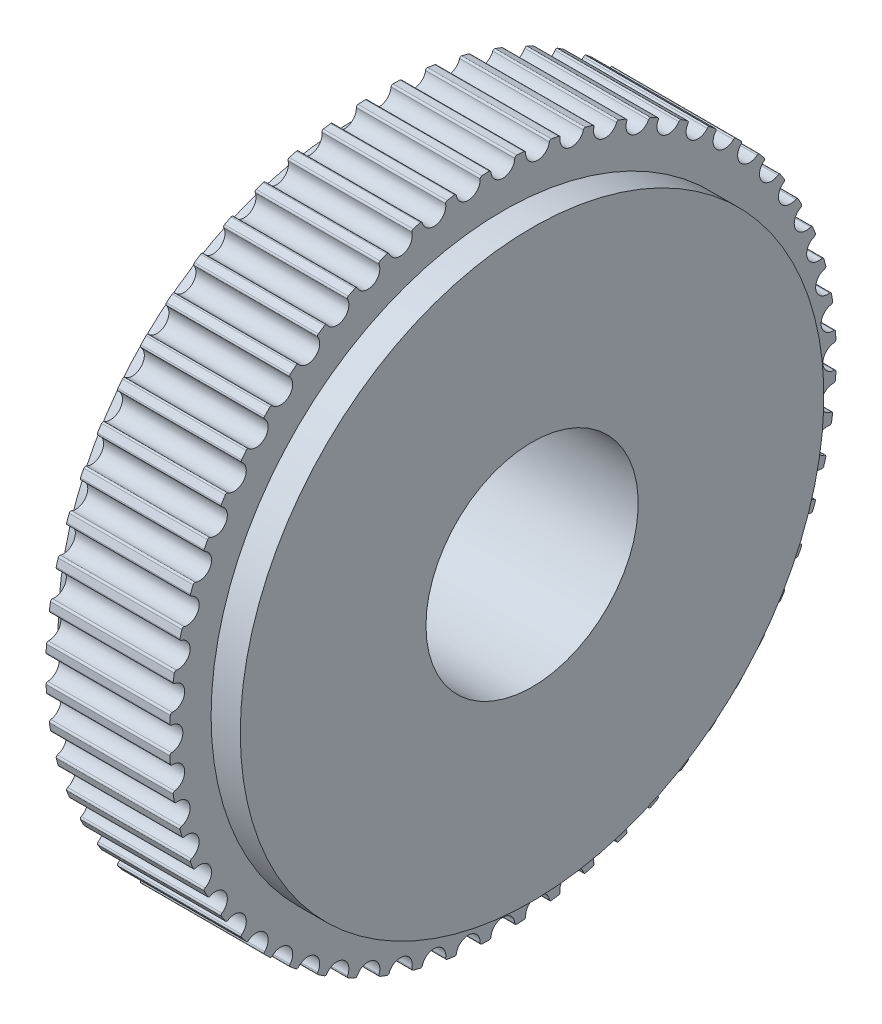
SolidWorks part; units mm, degrees
ref_plane "Front Plane" through (0, 0, 0) normal (0, 0, 1) x (1, 0, 0)
ref_plane "Top Plane" through (0, 0, 0) normal (0, 1, 0) x (1, 0, 0)
ref_plane "Right Plane" through (0, 0, 0) normal (1, 0, 0) x (0, 0, -1)
sketch "Sketch1" plane through (0, 0, 0) normal (0, 0, 1) x (1, 0, 0)
  line L0 (1.65, 19.1) -> (8.65, 19.1) construction
  line L1 (1.65, 18.845) -> (8.65, 18.845)
  line L2 (0, 16.5) -> (0, 6)
  line L4 (10.3, 16.5) -> (10.3, 6)
  line L5 (0, 6) -> (10.3, 6)
  line L6 (0, 0) -> (10.3, 0) construction
  line L8 (1.65, 16.5) -> (0, 16.5)
  line L9 (8.65, 16.5) -> (8.65, 18.845)
  line L10 (10.3, 16.5) -> (8.65, 16.5)
  line L13 (1.65, 16.5) -> (1.65, 18.845)
  dimension "W" = 10.3
  dimension "A" = 7
  dimension "E" = 33
  dimension "P.D." = 38.2
  dimension "H" = 12
revolve "Revolve1" add sketch "Sketch1" angle 360 about L6
sketch "Sketch2" plane through (1.65, 0, 0) normal (1, 0, 0) x (0, 0, -1)
  line L0 (0, 0) -> (0, 18.845) construction
  circle A0 centre (0, 0) radius 18.845 construction
  circle A1 centre (0, 0) radius 18.845 construction
  arc A2 (0.6721, 18.833) -> (-0.6721, 18.833) centre (0, 0) ccw
  arc A3 (-0.6721, 18.833) -> (0.6721, 18.833) centre (0, 18.77) ccw
  circle A6 centre (0, 0) radius 18.095 construction
  circle A7 centre (0, 0) radius 19.099 construction
  dimension "MSM_3" = 0.675
  dimension "MSM_2" = 0.254
  dimension "MSM_1" = 0.75
extrude "Cut-Extrude1" cut sketch "Sketch2" along normal through all
fillet "Fillet1" radius 0.1 2 edges at (5.15, 18.833, -0.6721) (5.15, 18.833, 0.6721)
pattern_circular "CirPattern1" count 60 over 360 about axis through (0, 0, 0) along (1, 0, 0) of "Cut-Extrude1", "Fillet1"
hole_wizard "Tapped Hole2" [suppressed] positions "Sketch9" profile "Sketch8" tap size "M3x0.5" standard "JIS"
sketch "Sketch9" [suppressed] plane through (10.3, 8.8848, 0.534) normal (1, 0, 0) x (0, 0, -1)
  line L2 (0.534, -8.8848) -> (0.534, -16.8848) construction
  line L3 (0.534, -8.8848) -> (-6.3942, -4.8848) construction
  circle A0 centre (0.534, -8.8848) radius 8 construction
  point P0 (0.534, -16.8848)
  point P23 (-6.3942, -4.8848)
  point P24 (7.4622, -4.8848)
  dimension "QTC" = 16
  dimension "Angle_2" = 120
  dimension "Number" = 3
sketch "Sketch8" [suppressed] plane through (10.3, -8, 0) normal (0, 1, 0) x (0, 0, -1)
  line L0 (0, 0) -> (0, 9.2511)
  line L1 (0, 9.2511) -> (1.25, 8.5)
  line L2 (1.25, 8.5) -> (1.25, 0)
  line L5 (1.25, 0) -> (0, 0)
  line L10 (0, 9.2511) -> (-1.25, 8.5) construction
  line L11 (0, 0) -> (0, 9.2511) construction
  dimension "Tap Drill Dia." = 2.5
  dimension "Tap Drill Depth" = 8.5
  dimension "Drill Angle" = 118
cosmetic thread "Hole Thread2" [suppressed] parameters "Mx2"=6, "M"=3
cosmetic thread "Hole Thread3" [suppressed] parameters "Mx2"=6, "M"=3
cosmetic thread "Hole Thread4" [suppressed] parameters "Mx2"=6, "M"=3
hole_wizard "Tapped Hole3" [suppressed] positions "Sketch11" profile "Sketch10" tap size "M3x0.5" standard "JIS"
sketch "Sketch11" [suppressed] plane through (10.3, 6.1168, -5.003) normal (1, 0, 0) x (0, 0, -1)
  line L3 (-5.003, -6.1168) -> (-10.6598, -11.7737) construction
  line L4 (-5.003, -6.1168) -> (-10.6598, -0.46) construction
  line L5 (-5.003, 1.8832) -> (-5.003, -14.1168) construction
  circle A0 centre (-5.003, -6.1168) radius 8 construction
  point P22 (-10.6598, -11.7737)
  point P23 (6.0104, 6.0104)
  point P27 (-10.6598, -0.46)
  point P28 (0.6539, -0.46)
  point P29 (0.6539, -11.7737)
  dimension "QFC" = 16
  dimension "Angle_2" = 90
  dimension "Angle_1" = 45
  dimension "Number" = 4
sketch "Sketch10" [suppressed] plane through (10.3, -5.6569, 5.6569) normal (0, 1, 0) x (0, 0, -1)
  line L0 (0, 0) -> (0, 9.2511)
  line L1 (0, 9.2511) -> (1.25, 8.5)
  line L2 (1.25, 8.5) -> (1.25, 0)
  line L5 (1.25, 0) -> (0, 0)
  line L10 (0, 9.2511) -> (-1.25, 8.5) construction
  line L11 (0, 0) -> (0, 9.2511) construction
  dimension "Tap Drill Dia." = 2.5
  dimension "Tap Drill Depth" = 8.5
  dimension "Drill Angle" = 118
cosmetic thread "Hole Thread5" [suppressed] parameters "Mx2"=6, "M"=3
cosmetic thread "Hole Thread6" [suppressed] parameters "Mx2"=6, "M"=3
cosmetic thread "Hole Thread7" [suppressed] parameters "Mx2"=6, "M"=3
cosmetic thread "Hole Thread8" [suppressed] parameters "Mx2"=6, "M"=3
hole_wizard "Tapped Hole4" [suppressed] positions "Sketch13" profile "Sketch12" tap size "M3x0.5" standard "JIS"
sketch "Sketch13" [suppressed] plane through (10.3, 0, 0) normal (1, 0, 0) x (0, 0, -1)
  line L0 (0, 0) -> (0, 8) construction
  line L2 (0, 0) -> (-3.3809, 7.2505) construction
  line L4 (0, 0) -> (4.5886, 6.5532) construction
  circle A0 centre (0, 0) radius 8 construction
  point P0 (-3.3809, 7.2505)
  point P33 (4.5886, 6.5532)
  point P34 (7.9696, -0.6972)
  point P35 (3.3809, -7.2505)
  point P36 (-4.5886, -6.5532)
  point P37 (-7.9696, 0.6972)
  point P38 (0, 0)
  dimension "QSC" = 16
  dimension "Angle_1" = 35
  dimension "Angle_2" = 60
  dimension "Number" = 6
sketch "Sketch12" [suppressed] plane through (10.3, 7.2505, 3.3809) normal (0, 1, 0) x (0, 0, -1)
  line L0 (0, 0) -> (0, 9.2511)
  line L1 (0, 9.2511) -> (1.25, 8.5)
  line L2 (1.25, 8.5) -> (1.25, 0)
  line L5 (1.25, 0) -> (0, 0)
  line L10 (0, 9.2511) -> (-1.25, 8.5) construction
  line L11 (0, 0) -> (0, 9.2511) construction
  dimension "Tap Drill Dia." = 2.5
  dimension "Tap Drill Depth" = 8.5
  dimension "Drill Angle" = 118
cosmetic thread "Hole Thread9" [suppressed] parameters "Mx2"=6, "M"=3
cosmetic thread "Hole Thread10" [suppressed] parameters "Mx2"=6, "M"=3
cosmetic thread "Hole Thread11" [suppressed] parameters "Mx2"=6, "M"=3
cosmetic thread "Hole Thread12" [suppressed] parameters "Mx2"=6, "M"=3
cosmetic thread "Hole Thread13" [suppressed] parameters "Mx2"=6, "M"=3
cosmetic thread "Hole Thread14" [suppressed] parameters "Mx2"=6, "M"=3
hole_wizard "Diameter Hole1" [suppressed] positions "Sketch15" profile "Sketch14" hole size "Ø4.0" standard "JIS"
sketch "Sketch15" [suppressed] plane through (0, 0, 0) normal (1, 0, 0) x (0, 0, -1)
  line L11 (0, 0) -> (0, -8) construction
  line L12 (0, 0) -> (-6.9282, 4) construction
  circle A2 centre (0, 0) radius 8 construction
  point P16 (0, -8)
  point P80 (-6.9282, 4)
  point P81 (6.9282, 4)
  dimension "D1" = 120
  dimension "KTC" = 16
  dimension "D2" = 3
sketch "Sketch14" [suppressed] plane through (0, -8, 0) normal (0, 1, 0) x (0, 0, 1)
  line L0 (0, 0) -> (0, 10.3)
  line L1 (0, 10.3) -> (2, 10.3)
  line L2 (2, 10.3) -> (2, 0)
  line L5 (2, 0) -> (0, 0)
  line L11 (0, 0) -> (0, 10.3) construction
  dimension "K" = 4
  dimension "Thru Hole Depth" = 10.3
hole_wizard "Diameter Hole2" [suppressed] positions "Sketch17" profile "Sketch16" hole size "Ø4.0" standard "JIS"
sketch "Sketch17" [suppressed] plane through (0, 0, 0) normal (1, 0, 0) x (0, 0, -1)
  line L18 (0, 0) -> (-5.6569, -5.6569) construction
  line L19 (0, 0) -> (-5.6569, 5.6569) construction
  line L20 (0, 8) -> (0, -8) construction
  circle A2 centre (0, 0) radius 8 construction
  point P104 (-5.6569, -5.6569)
  point P120 (-6.364, 6.364)
  point P146 (-5.6569, 5.6569)
  point P147 (5.6569, 5.6569)
  point P148 (5.6569, -5.6569)
  dimension "D1" = 90
  dimension "KFC" = 16
  dimension "D2" = 45
  dimension "D3" = 4
sketch "Sketch16" [suppressed] plane through (0, -5.6569, 5.6569) normal (0, 1, 0) x (0, 0, 1)
  line L0 (0, 0) -> (0, 10.3)
  line L1 (0, 10.3) -> (2, 10.3)
  line L2 (2, 10.3) -> (2, 0)
  line L5 (2, 0) -> (0, 0)
  line L11 (0, 0) -> (0, 10.3) construction
  dimension "K" = 4
  dimension "Thru Hole Depth" = 10.3
hole_wizard "Diameter Hole3" [suppressed] positions "Sketch19" profile "Sketch18" hole size "Ø4.0" standard "JIS"
sketch "Sketch19" [suppressed] plane through (0, 0, 0) normal (-1, 0, 0) x (0, 0, 1)
  line L0 (0, 8) -> (0, 0) construction
  line L1 (0, 0) -> (3.3809, 7.2505) construction
  line L3 (0, 0) -> (-4.5886, 6.5532) construction
  circle A0 centre (0, 0) radius 8 construction
  point P0 (-4.5886, 6.5532)
  point P23 (3.3809, 7.2505)
  point P24 (7.9696, 0.6972)
  point P25 (4.5886, -6.5532)
  point P26 (-3.3809, -7.2505)
  point P27 (-7.9696, -0.6972)
  point P28 (0, 0)
  dimension "D3" = 6
  dimension "KSC" = 16
  dimension "D1" = 35
  dimension "D2" = 60
sketch "Sketch18" [suppressed] plane through (0, 6.5532, -4.5886) normal (0, 1, 0) x (0, 0, 1)
  line L0 (0, 0) -> (0, 10.3)
  line L1 (0, 10.3) -> (2, 10.3)
  line L2 (2, 10.3) -> (2, 0)
  line L5 (2, 0) -> (0, 0)
  line L11 (0, 0) -> (0, 10.3) construction
  dimension "K" = 4
  dimension "Thru Hole Depth" = 10.3
hole_wizard "CBORE for Socket Head Cap Screw1" [suppressed] positions "Sketch21" profile "Sketch20" counterbore size "M3" standard "JIS"
sketch "Sketch21" [suppressed] plane through (0, 0, 0) normal (-1, 0, 0) x (0, 0, 1)
  line L2 (0, 0) -> (0, -9.25) construction
  line L4 (0, 0) -> (8.0107, 4.625) construction
  circle A0 centre (0, 0) radius 9.25 construction
  circle A1 centre (8.0107, 4.625) radius 1.5 construction
  point P0 (0, -9.25)
  point P38 (-8.0107, 4.625)
  point P39 (8.0107, 4.625)
  dimension "ZTC" = 18.5
  dimension "D2" = 120
  dimension "D1" = 3
  dimension "ZM" = 3
sketch "Sketch20" [suppressed] plane through (0, -9.25, 0) normal (0, 1, 0) x (0, 0, 1)
  line L0 (0, 0) -> (0, 10.3)
  line L1 (0, 10.3) -> (1.7, 10.3)
  line L3 (1.7, 10.3) -> (1.7, 3)
  line L4 (1.7, 3) -> (3.25, 3)
  line L5 (3.25, 3) -> (3.25, 0)
  line L7 (3.25, 0) -> (0, 0)
  line L11 (0, 0) -> (0, 10.3) construction
  dimension "D1_s" = 3.4
  dimension "Thru Hole Depth" = 10.3
  dimension "D2_s" = 6.5
  dimension "H_s" = 3
hole_wizard "CBORE for Socket Head Cap Screw2" [suppressed] positions "Sketch23" profile "Sketch22" counterbore size "M3" standard "JIS"
sketch "Sketch23" [suppressed] plane through (0, 0, 0) normal (-1, 0, 0) x (0, 0, 1)
  line L0 (0, 0) -> (0, 9.25) construction
  line L2 (6.5407, 6.5407) -> (0, 0) construction
  line L3 (0, 0) -> (6.5407, -6.5407) construction
  circle A0 centre (0, 0) radius 9.25 construction
  circle A1 centre (6.5407, 6.5407) radius 1.5 construction
  point P0 (6.5407, 6.5407)
  point P31 (6.5407, -6.5407)
  point P32 (-6.5407, -6.5407)
  point P33 (-6.5407, 6.5407)
  dimension "ZFC" = 18.5
  dimension "D2" = 45
  dimension "D3" = 90
  dimension "D1" = 4
  dimension "ZM" = 3
sketch "Sketch22" [suppressed] plane through (0, 6.5407, 6.5407) normal (0, 1, 0) x (0, 0, 1)
  line L0 (0, 0) -> (0, 10.3)
  line L1 (0, 10.3) -> (1.75, 10.3)
  line L3 (1.75, 10.3) -> (1.75, 3.5)
  line L4 (1.75, 3.5) -> (3.25, 3.5)
  line L5 (3.25, 3.5) -> (3.25, 0)
  line L7 (3.25, 0) -> (0, 0)
  line L11 (0, 0) -> (0, 10.3) construction
  dimension "D1_s" = 3.5
  dimension "Thru Hole Depth" = 10.3
  dimension "D2_s" = 6.5
  dimension "H_s" = 3.5
hole_wizard "CBORE for Socket Head Cap Screw3" [suppressed] positions "Sketch25" profile "Sketch24" counterbore size "M3" standard "JIS"
sketch "Sketch25" [suppressed] plane through (0, 0, 0) normal (-1, 0, 0) x (0, 0, 1)
  line L0 (0, 0) -> (0, 9.25) construction
  line L2 (0, 0) -> (-5.3056, 7.5772) construction
  line L4 (0, 0) -> (3.9092, 8.3833) construction
  circle A0 centre (0, 0) radius 9.25 construction
  circle A1 centre (3.9092, 8.3833) radius 1.5 construction
  point P0 (-5.3056, 7.5772)
  point P32 (3.9092, 8.3833)
  point P33 (9.2148, 0.8062)
  point P34 (5.3056, -7.5772)
  point P35 (-3.9092, -8.3833)
  point P36 (-9.2148, -0.8062)
  dimension "ZSC" = 18.5
  dimension "D2" = 35
  dimension "D3" = 60
  dimension "D1" = 6
  dimension "ZM" = 3
sketch "Sketch24" [suppressed] plane through (0, 7.5772, -5.3056) normal (0, 1, 0) x (0, 0, 1)
  line L0 (0, 0) -> (0, 10.3)
  line L1 (0, 10.3) -> (1.75, 10.3)
  line L3 (1.75, 10.3) -> (1.75, 3.5)
  line L4 (1.75, 3.5) -> (3.25, 3.5)
  line L5 (3.25, 3.5) -> (3.25, 0)
  line L7 (3.25, 0) -> (0, 0)
  line L11 (0, 0) -> (0, 10.3) construction
  dimension "D1_s" = 3.5
  dimension "Thru Hole Depth" = 10.3
  dimension "D2_s" = 6.5
  dimension "H_s" = 3.5
equation "\"Plane dim\"= \"O.D.@Sketch1\" * 0.5"
equation "\"ZM\"=3.000000"
